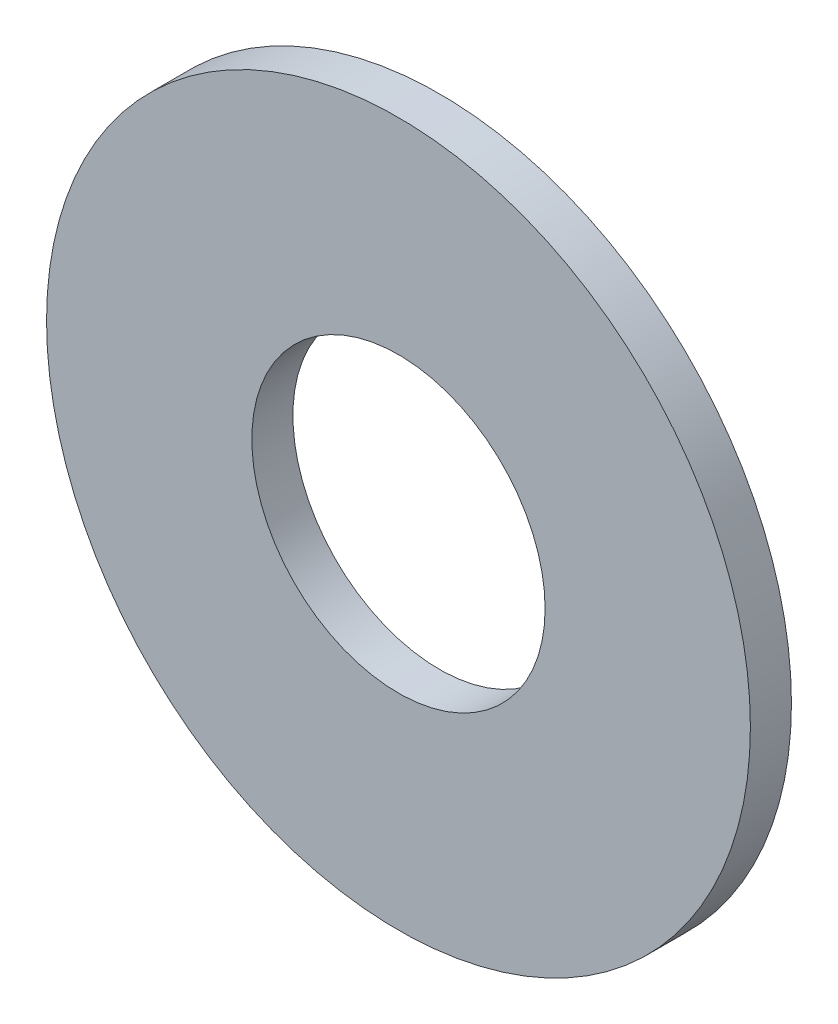
SolidWorks part; units mm, degrees
material "ABS"
ref_plane "Front Plane" through (0, 0, 0) normal (0, 0, 1) x (1, 0, 0)
ref_plane "Top Plane" through (0, 0, 0) normal (0, 1, 0) x (1, 0, 0)
ref_plane "Right Plane" through (0, 0, 0) normal (1, 0, 0) x (0, 0, -1)
sketch "Sketch1" plane through (0, 0, 0) normal (0, 0, 1) x (1, 0, 0)
  circle A0 centre (0, 0) radius 12
  circle A1 centre (0, 0) radius 5
  dimension "D1" = 24
  dimension "D2" = 10
extrude "Boss-Extrude1" add sketch "Sketch1" along normal blind 1.4
